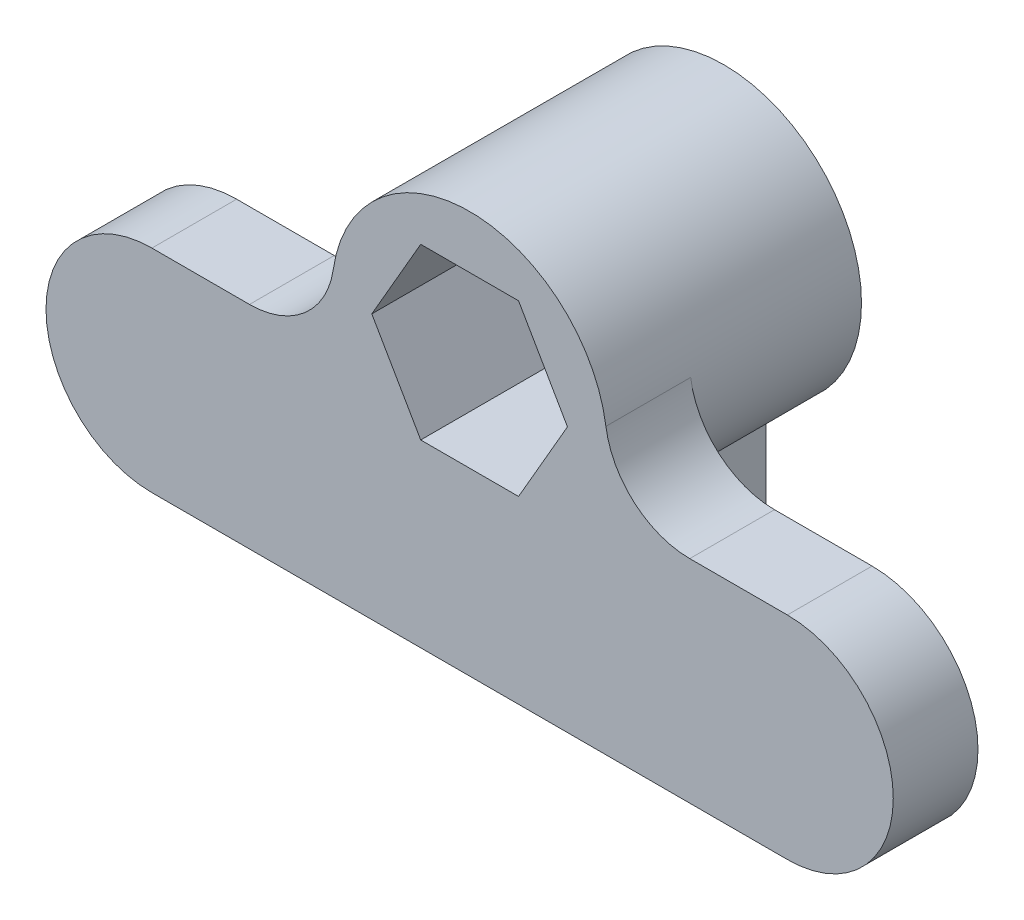
SolidWorks part; units mm, degrees
ref_plane "Front Plane" through (0, 0, 0) normal (0, 0, 1) x (1, 0, 0)
ref_plane "Top Plane" through (0, 0, 0) normal (0, 1, 0) x (1, 0, 0)
ref_plane "Right Plane" through (0, 0, 0) normal (1, 0, 0) x (0, 0, -1)
sketch "Sketch1" plane through (0, 0, 0) normal (0, 0, 1) x (1, 0, 0)
  line L0 (-7.5, -3.75) -> (7.5, -3.75) construction
  line L1 (-7.5, -1.25) -> (-3, -1.25)
  line L2 (-7.5, -6.25) -> (7.5, -6.25)
  line L3 (0, -3.75) -> (0, 0) construction
  line L4 (3, -1.25) -> (7.5, -1.25)
  circle A0 centre (0, 0) radius 1.25
  arc A1 (3, -1.25) -> (-3, -1.25) centre (0, 0) ccw
  arc A2 (-7.5, -1.25) -> (-7.5, -6.25) centre (-7.5, -3.75) ccw
  arc A3 (7.5, -6.25) -> (7.5, -1.25) centre (7.5, -3.75) ccw
  circle A4 centre (0, 0) radius 3.25 construction
  point P7 (0, -3.75)
  dimension "D2" = 2.5
  dimension "D4" = 2.5
  dimension "D3" = 15
  dimension "D1" = 2
extrude "Boss-Extrude1" add sketch "Sketch1" along normal blind 2
sketch "Sketch2" plane through (0, 0, 2) normal (0, 0, 1) x (1, 0, 0)
  line L0 (-3, -1.25) -> (-7.5, -1.25) construction
  line L1 (-3, -1.25) -> (-8, -1.25)
  line L2 (-3, -1.25) -> (-3, -6.25)
  line L3 (-3, -6.25) -> (-8, -6.25)
  line L4 (-8, -1.25) -> (-8, -6.25)
  line L5 (-7.5, -6.25) -> (7.5, -6.25) construction
  line L6 (7.5, -1.25) -> (3, -1.25) construction
  line L7 (3, -1.25) -> (8, -1.25)
  line L8 (3, -1.25) -> (3, -6.25)
  line L9 (3, -6.25) -> (8, -6.25)
  line L10 (8, -1.25) -> (8, -6.25)
  line L11 (-8, -3.75) -> (-10, -3.75) construction
  line L12 (8, -3.75) -> (10, -3.75) construction
  line L16 (-3, -1.25) -> (-7.5, -1.25)
  line L17 (-7.5, -6.25) -> (7.5, -6.25)
  line L18 (7.5, -1.25) -> (3, -1.25)
  line L19 (-3, -1.25) -> (-7.5, -1.25)
  line L20 (-7.5, -6.25) -> (7.5, -6.25)
  line L21 (7.5, -1.25) -> (3, -1.25)
  arc A0 (-7.5, -1.25) -> (-7.5, -6.25) centre (-7.5, -3.75) ccw construction
  arc A1 (7.5, -6.25) -> (7.5, -1.25) centre (7.5, -3.75) ccw construction
  circle A2 centre (0, 0) radius 3.25
  circle A3 centre (0, 0) radius 3.45
  arc A5 (3, -1.25) -> (-3, -1.25) centre (0, 0) ccw
  arc A6 (-7.5, -1.25) -> (-7.5, -6.25) centre (-7.5, -3.75) ccw
  arc A7 (7.5, -6.25) -> (7.5, -1.25) centre (7.5, -3.75) ccw
  arc A8 (3, -1.25) -> (-3, -1.25) centre (0, 0) ccw
  arc A9 (-7.5, -1.25) -> (-7.5, -6.25) centre (-7.5, -3.75) ccw
  arc A10 (7.5, -6.25) -> (7.5, -1.25) centre (7.5, -3.75) ccw
  arc M20 (-7.5, -1.25) -> (-7.5, -6.25) centre (-7.5, -3.75) ccw
  line M21 (-7.5, -6.25) -> (7.5, -6.25)
  arc M22 (7.5, -6.25) -> (7.5, -1.25) centre (7.5, -3.75) ccw
  dimension "D1" = 5
  dimension "D2" = 5
  dimension "D3" = 0
  dimension "D4" = 0.2
extrude "Boss-Extrude2" add sketch "Sketch2" along normal blind 4 contours L4 M20 | A3 L2 L8 M21 | L10 M22
fillet "Fillet1" radius 2 2 edges at (3, -1.25, 1) (-3, -1.25, 1)
sketch "Sketch3" plane through (0, 0, 2) normal (0, 0, 1) x (1, 0, 0)
  line L0 (-3, -6.25) -> (3, -6.25) construction
  line L2 (-1, -3.0923) -> (-1, -6.25)
  line L3 (-1, -6.25) -> (1, -6.25)
  line L4 (1, -3.0923) -> (1, -6.25)
  line L5 (0, 0) -> (0, -6.25) construction
  arc A0 (1, -3.0923) -> (-1, -3.0923) centre (0, 0) ccw
  arc A1 (3.2167, 0.4643) -> (-3.2167, 0.4643) centre (0, 0) ccw construction
  circle A2 centre (0, 0) radius 1.25 construction
  circle A3 centre (0, 0) radius 1.25
  dimension "D1" = 2
extrude "Boss-Extrude3" add sketch "Sketch3" along normal blind 4 separate body
sketch "Sketch4" plane through (0, 0, 6) normal (0, 0, 1) x (1, 0, 0)
  line L3 (7.5, -1.25) -> (5.1962, -1.25)
  line L4 (-7.5, -6.25) -> (7.5, -6.25)
  line L5 (-5.1962, -1.25) -> (-7.5, -1.25)
  line L6 (7.5, -1.25) -> (5.1962, -1.25)
  line L7 (-7.5, -6.25) -> (7.5, -6.25)
  line L8 (-5.1962, -1.25) -> (-7.5, -1.25)
  arc A0 (8, -6.1995) -> (8, -1.3005) centre (7.5, -3.75) ccw construction
  arc A1 (8, -6.1995) -> (8, -1.3005) centre (7.5, -3.75) ccw
  circle A2 centre (0, 0) radius 1.25 construction
  circle A3 centre (0, 0) radius 1.25
  arc A7 (3.2167, 0.4643) -> (-3.2167, 0.4643) centre (0, 0) ccw
  arc A8 (3.2167, 0.4643) -> (5.1962, -1.25) centre (5.1962, 0.75) ccw
  arc A9 (7.5, -6.25) -> (7.5, -1.25) centre (7.5, -3.75) ccw
  arc A10 (-7.5, -1.25) -> (-7.5, -6.25) centre (-7.5, -3.75) ccw
  arc A11 (-5.1962, -1.25) -> (-3.2167, 0.4643) centre (-5.1962, 0.75) ccw
  arc A12 (3.2167, 0.4643) -> (-3.2167, 0.4643) centre (0, 0) ccw
  arc A13 (3.2167, 0.4643) -> (5.1962, -1.25) centre (5.1962, 0.75) ccw
  arc A14 (7.5, -6.25) -> (7.5, -1.25) centre (7.5, -3.75) ccw
  arc A15 (-7.5, -1.25) -> (-7.5, -6.25) centre (-7.5, -3.75) ccw
  arc A16 (-5.1962, -1.25) -> (-3.2167, 0.4643) centre (-5.1962, 0.75) ccw
  arc M9 (1, -3.0923) -> (-1, -3.0923) centre (0, 0) ccw
  circle M10 centre (0, 0) radius 1.25
  dimension "D1" = 0
delete or keep bodies "Body-Delete/Keep 1" type delete bodies bodies 102
extrude "Boss-Extrude4" add sketch "Sketch4" along normal blind 2 contours A16 L8 A15 L7 A14 A1 L6 A13 M9 | M9 M10
sketch "Sketch5" plane through (0, 0, 8) normal (0, 0, 1) x (1, 0, 0)
  line L1 (1.1547, 2) -> (-1.1547, 2)
  line L2 (-1.1547, 2) -> (-2.3094, 0)
  line L3 (-2.3094, 0) -> (-1.1547, -2)
  line L4 (-1.1547, -2) -> (1.1547, -2)
  line L5 (1.1547, -2) -> (2.3094, 0)
  line L6 (2.3094, 0) -> (1.1547, 2)
  circle A0 centre (0, 0) radius 2 construction
  dimension "D1" = 4
extrude "Cut-Extrude1" cut sketch "Sketch5" against normal offset from surface (4 mm away) 2 up to face at (0, -3.0856, 2)
